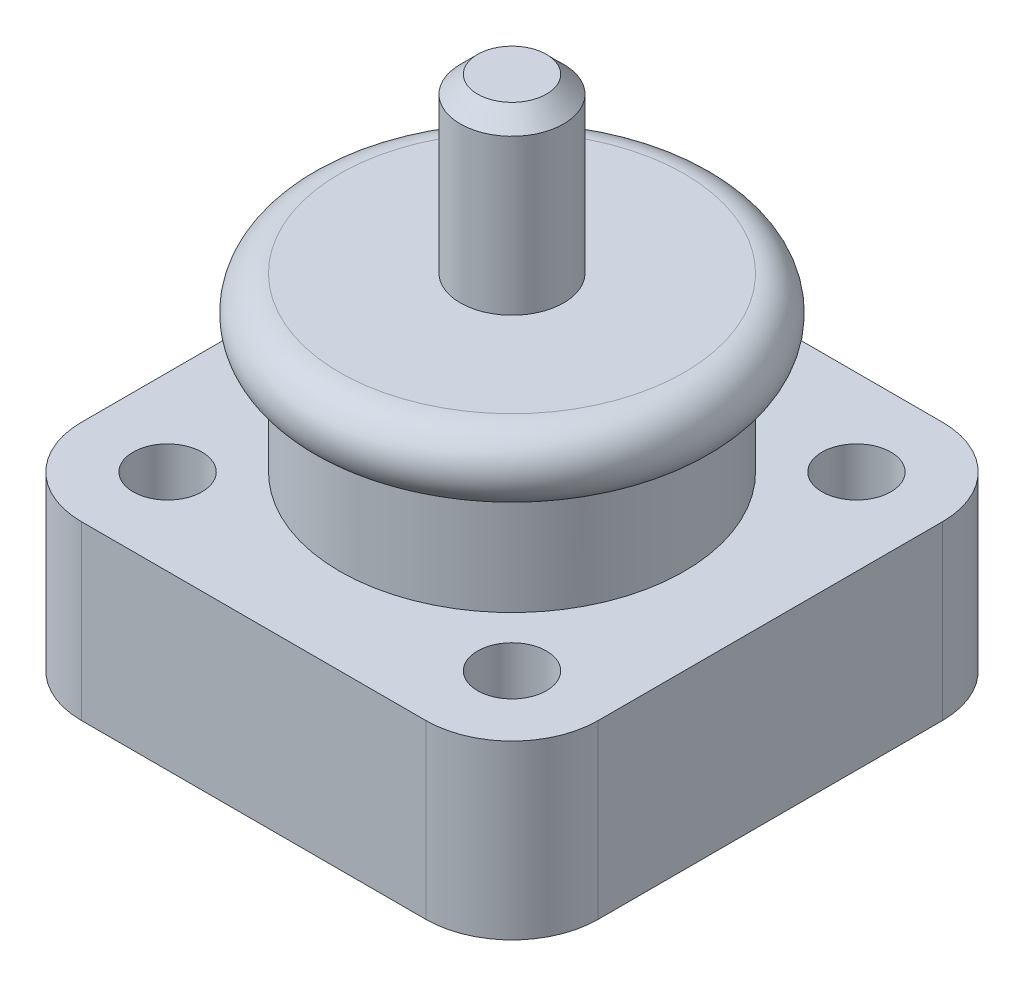
SolidWorks part; units mm, degrees
ref_plane "Front Plane" through (0, 0, 0) normal (0, 0, 1) x (1, 0, 0)
ref_plane "Top Plane" through (0, 0, 0) normal (0, 1, 0) x (1, 0, 0)
ref_plane "Right Plane" through (0, 0, 0) normal (1, 0, 0) x (0, 0, -1)
sketch "Sketch1" plane through (0, 0, 0) normal (0, 1, 0) x (1, 0, 0)
  line L1 (-10, -15) -> (10, -15)
  line L2 (-15, -10) -> (-15, 10)
  line L3 (-10, 15) -> (10, 15)
  line L4 (15, -10) -> (15, 10)
  line L5 (-15, -15) -> (15, 15) construction
  line L6 (-15, 15) -> (15, -15) construction
  arc A0 (10, -15) -> (15, -10) centre (10, -10) ccw
  arc A1 (-10, -15) -> (-15, -10) centre (-10, -10) cw
  arc A2 (-15, 10) -> (-10, 15) centre (-10, 10) cw
  arc A3 (15, 10) -> (10, 15) centre (10, 10) ccw
  circle A4 centre (-10, 10) radius 2
  circle A5 centre (10, 10) radius 2
  circle A6 centre (-10, -10) radius 2
  circle A7 centre (10, -10) radius 2
  point P0 (0, 0)
  point P5 (0, 0)
  dimension "D3" = 5
  dimension "D4" = 2
  dimension "D5" = 2
  dimension "D6" = 2
  dimension "D7" = 2
  dimension "D1" = 30
  dimension "D2" = 30
extrude "Boss-Extrude1" add sketch "Sketch1" along normal blind 10
sketch "Sketch2" plane through (0, 10, 0) normal (0, 1, 0) x (1, 0, 0)
  circle A0 centre (0, 0) radius 10
  point P2 (0.3413, -4.385)
  dimension "D1" = 10
extrude "Boss-Extrude2" add sketch "Sketch2" along normal blind 10
sketch "Sketch3" plane through (0, 0, 0) normal (1, 0, 0) x (0, 0, -1)
  line L0 (10, 20) -> (-10, 20) construction
  line L1 (-10, 20) -> (-10, 10) construction
  line L2 (0, 0) -> (0, 21.3826) construction
  circle A0 centre (-10, 18) radius 2
  point P4 (0, 4.2174)
  dimension "D1" = 2
revolve "Revolve1" add sketch "Sketch3" angle 360 about L2
sketch "Sketch4" plane through (0, 20, 0) normal (0, 1, 0) x (1, 0, 0)
  circle A0 centre (0, 0) radius 3
  point P2 (1.024, -2.1794)
  dimension "D1" = 3
extrude "Boss-Extrude3" add sketch "Sketch4" along normal blind 10
cosmetic thread "Cosmetic Thread1" parameters "D2"=4.891
chamfer "Chamfer1" distance 1 angle 45 1 edges at (0, 30, 3)
sketch "Sketch5" plane through (0, 0, 0) normal (0, -1, 0) x (1, 0, 0)
  circle A0 centre (0, 0) radius 8
  dimension "D1" = 8
extrude "Cut-Extrude1" cut sketch "Sketch5" against normal blind 2
